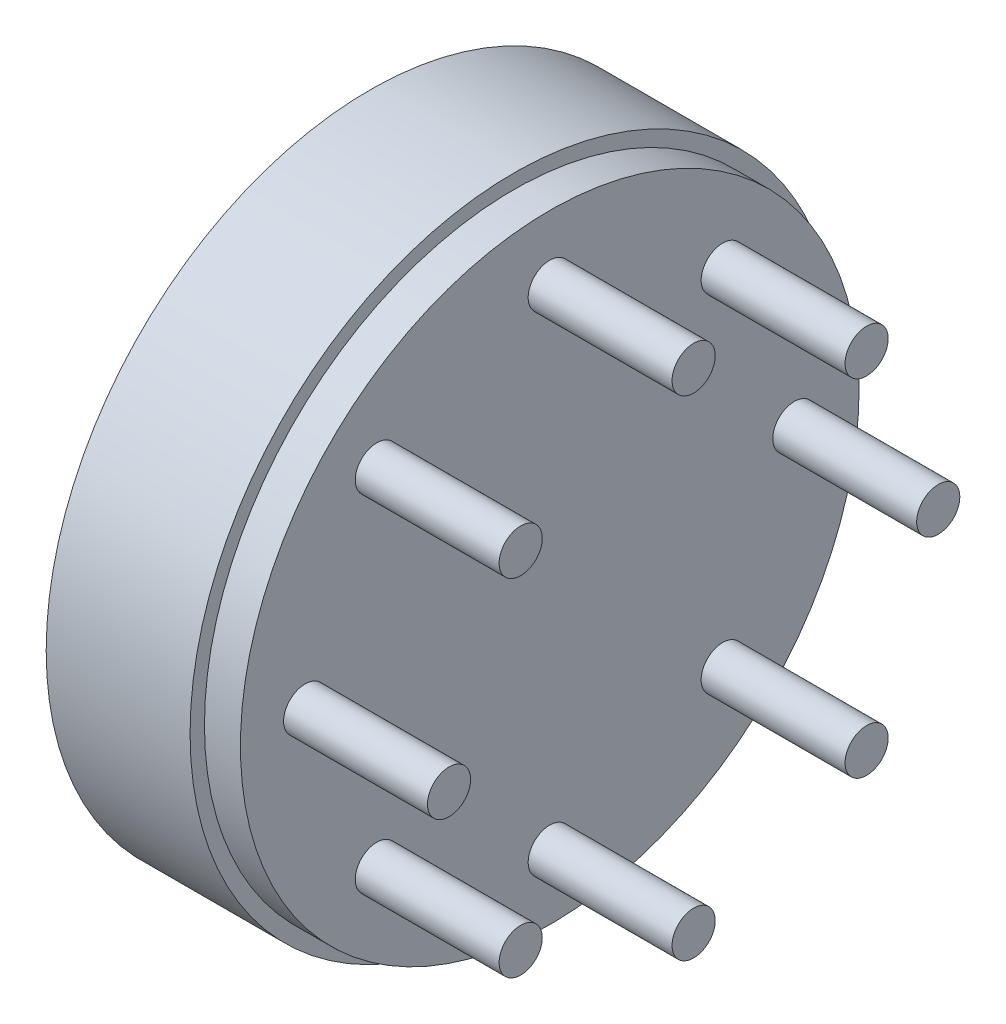
SolidWorks part; units mm, degrees
ref_plane "Front Plane" through (0, 0, 0) normal (0, 0, 1) x (1, 0, 0)
ref_plane "Top Plane" through (0, 0, 0) normal (0, 1, 0) x (1, 0, 0)
ref_plane "Right Plane" through (0, 0, 0) normal (1, 0, 0) x (0, 0, -1)
ref_plane "Plane1" through (1124.08, 0, 0) normal (1, 0, 0) x (0, 0, -1)
sketch "Sketch2" plane through (1124.08, 0, 0) normal (1, 0, 0) x (0, 0, -1)
  circle A0 centre (0, 0) radius 215
  dimension "D1" = 430
extrude "Boss-Extrude1" add sketch "Sketch2" against normal blind 25
sketch "Sketch3" plane through (1099.08, 0, 0) normal (-1, 0, 0) x (0, 0, 1)
  circle A0 centre (0, 0) radius 225
  dimension "D1" = 450
extrude "Boss-Extrude2" add sketch "Sketch3" along normal blind 100
sketch "Sketch5" plane through (1124.08, 0, 0) normal (1, 0, 0) x (0, 0, -1)
  circle A0 centre (0, 170) radius 15
  circle A1 centre (120.2082, 120.2082) radius 15
  circle A2 centre (170, 0) radius 15
  circle A3 centre (120.2082, -120.2082) radius 15
  circle A4 centre (0, -170) radius 15
  circle A5 centre (-120.2082, -120.2082) radius 15
  circle A6 centre (-170, 0) radius 15
  circle A7 centre (-120.2082, 120.2082) radius 15
  dimension "D1" = 30
  dimension "D2" = 170
  dimension "D3" = 8
extrude "Boss-Extrude3" add sketch "Sketch5" along normal blind 100
